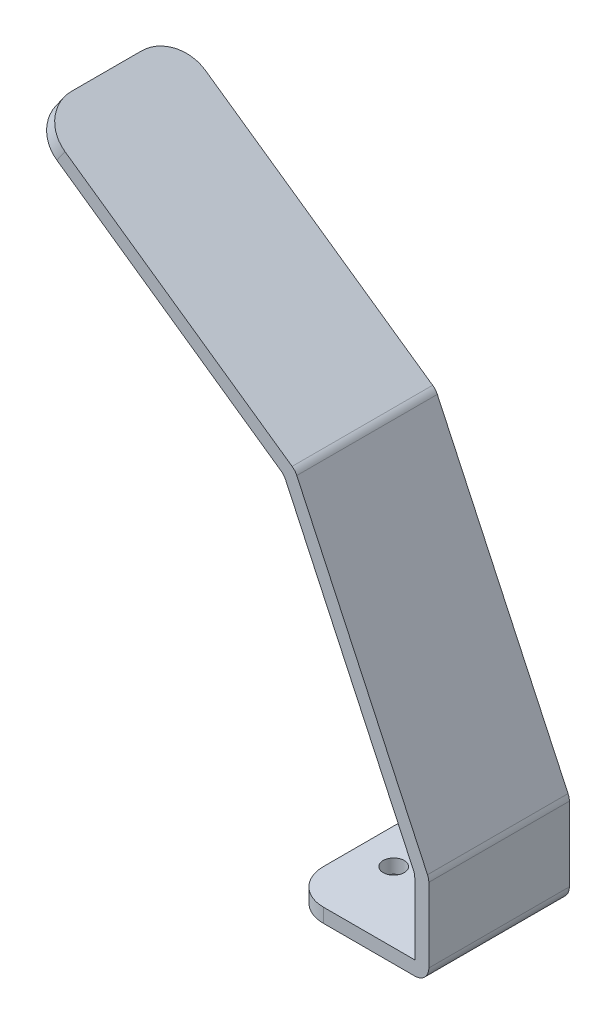
SolidWorks part; units mm, degrees
material "1060 Alloy"
ref_plane "Front Plane" through (0, 0, 0) normal (0, 0, 1) x (1, 0, 0)
ref_plane "Top Plane" through (0, 0, 0) normal (0, 1, 0) x (1, 0, 0)
ref_plane "Right Plane" through (0, 0, 0) normal (1, 0, 0) x (0, 0, -1)
sketch "Sketch1" plane through (0, 0, 0) normal (0, 0, 1) x (1, 0, 0)
  line L0 (0, 0) -> (20, 0)
  line L1 (20, 0) -> (20, 13)
  line L2 (20, 13) -> (0.9822, 53.7839)
  line L8 (0.9822, 53.7839) -> (-35.8797, 79.5948)
  line L9 (0, 2) -> (18, 2)
  line L10 (18, 2) -> (18, 12.5566)
  line L11 (18, 12.5566) -> (-0.604, 52.4529)
  line L12 (-0.604, 52.4529) -> (-37.0268, 77.9565)
  line L13 (0, 0) -> (0, 2)
  line L14 (-35.8797, 79.5948) -> (-37.0268, 77.9565)
  dimension "D1" = 20
  dimension "D2" = 155
  dimension "D3" = 13
  dimension "D4" = 35
  dimension "D6" = 45
  dimension "D7" = 45
  dimension "D5" = 2
extrude "Boss-Extrude1" add sketch "Sketch1" along normal mid plane 20
fillet "Fillet1" radius 2 5 edges at (20, 0, 0) (20, 13, 0) (-0.604, 52.4529, 0) (0.9822, 53.7839, 0) (18, 12.5566, 0)
fillet "Fillet2" radius 5 4 edges at (0, 1, 10) (0, 1, -10) (-36.4532, 78.7756, -10) (-36.4532, 78.7756, 10)
sketch "Sketch2" plane through (0, 0, 0) normal (0, -1, 0) x (1, 0, 0)
  line L0 (-4.6031, 0) -> (23.894, 0) construction
  line L2 (0, 5) -> (0, -5) construction
  circle A0 centre (5, 0) radius 1.5
  circle A1 centre (15, 0) radius 1.5
  dimension "D1" = 3
  dimension "D3" = 10
  dimension "D2" = 5
extrude "Cut-Extrude1" cut sketch "Sketch2" against normal blind 3
